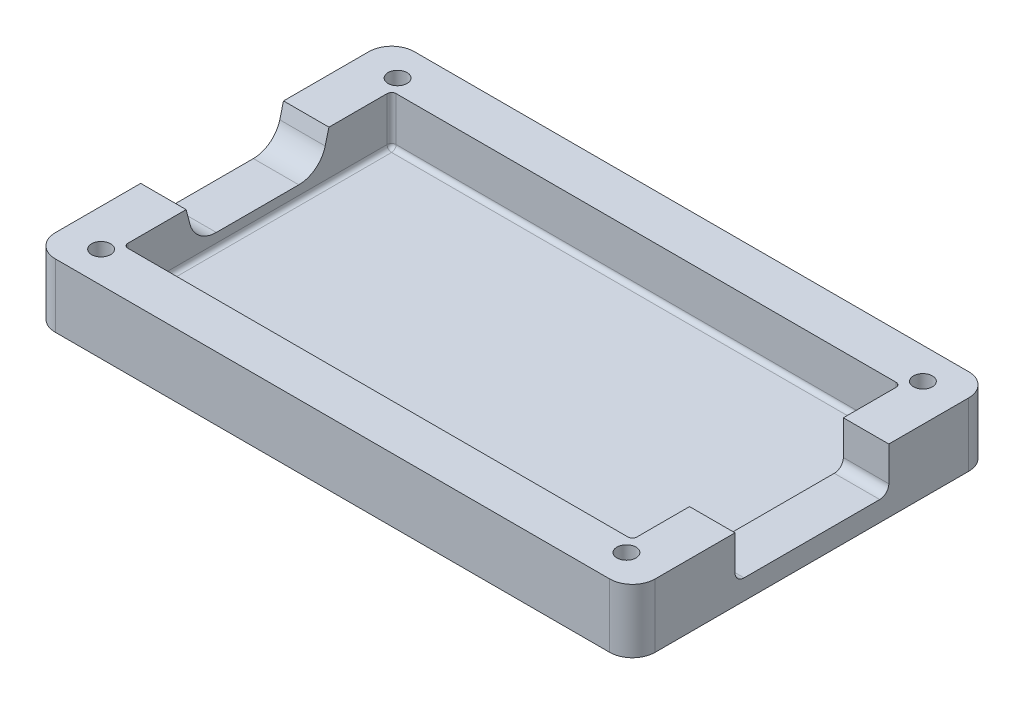
SolidWorks part; units mm, degrees
material "ABS"
ref_plane "Front Plane" through (0, 0, 0) normal (0, 0, 1) x (1, 0, 0)
ref_plane "Top Plane" through (0, 0, 0) normal (0, 1, 0) x (1, 0, 0)
ref_plane "Right Plane" through (0, 0, 0) normal (1, 0, 0) x (0, 0, -1)
sketch "Sketch1" plane through (0, 0, 0) normal (0, 1, 0) x (1, 0, 0)
  line L1 (-16.764, -10.033) -> (16.764, -10.033)
  line L2 (-16.764, -10.033) -> (-16.764, 10.033)
  line L3 (-16.764, 10.033) -> (16.764, 10.033)
  line L4 (16.764, -10.033) -> (16.764, 10.033)
  line L5 (-16.764, -10.033) -> (16.764, 10.033) construction
  line L6 (-16.764, 10.033) -> (16.764, -10.033) construction
  point P0 (0, 0)
  dimension "D1" = 20.066
  dimension "D2" = 33.528
extrude "Boss-Extrude1" add sketch "Sketch1" along normal blind 3.556
sketch "Sketch2" plane through (0, 3.556, 0) normal (0, 1, 0) x (1, 0, 0)
  line L1 (-14.224, -7.493) -> (14.224, -7.493)
  line L2 (-14.224, -7.493) -> (-14.224, 7.493)
  line L3 (-14.224, 7.493) -> (14.224, 7.493)
  line L4 (14.224, -7.493) -> (14.224, 7.493)
  line L5 (-14.224, -7.493) -> (14.224, 7.493) construction
  line L6 (-14.224, 7.493) -> (14.224, -7.493) construction
  point P0 (0, 0)
  dimension "D1" = 14.986
  dimension "D2" = 28.448
extrude "Cut-Extrude1" cut sketch "Sketch2" against normal blind 2.722
sketch "Sketch3" plane through (16.764, 0, 0) normal (1, 0, 0) x (0, 0, -1)
  line L0 (-10.033, 3.556) -> (10.033, 3.556) construction
  line L1 (-4.2995, 3.556) -> (4.2995, 3.556)
  line L2 (-4.2995, 3.556) -> (-4.2995, 1.1218)
  line L3 (-4.2995, 1.1218) -> (4.2995, 1.1218)
  line L4 (4.2995, 3.556) -> (4.2995, 1.1218)
  line L5 (-10.033, 0) -> (10.033, 0) construction
  point P6 (0, 1.1218)
  point P11 (0, 0)
extrude "Cut-Extrude2" cut sketch "Sketch3" against normal up to next
sketch "Sketch5" plane through (-16.764, 0, 0) normal (-1, 0, 0) x (0, 0, 1)
  line L0 (-3.9914, 3.556) -> (3.9914, 3.556)
  line L1 (-10.033, 3.556) -> (10.033, 3.556) construction
  line L2 (-10.033, 0) -> (10.033, 0) construction
  line L3 (-3.4845, 1.6072) -> (3.4845, 1.6072)
  line L4 (3.4845, 1.6072) -> (3.9914, 3.556)
  line L5 (-3.9914, 3.556) -> (-3.4845, 1.6072)
  point P4 (0, 3.556)
  point P7 (0, 0)
  point P8 (0, 1.6072)
extrude "Cut-Extrude3" cut sketch "Sketch5" against normal up to next
fillet "Fillet1" radius 1.524 2 edges at (-15.494, 1.6072, 3.4845) (-15.494, 1.6072, -3.4845)
fillet "Fillet2" radius 0.508 2 edges at (15.494, 1.1218, -4.2995) (15.494, 1.1218, 4.2995)
fillet "Fillet3" radius 1.27 4 edges at (-16.764, 1.778, -10.033) (-16.764, 1.778, 10.033) (16.764, 1.778, 10.033) (16.764, 1.778, -10.033)
sketch "Sketch7" plane through (0, 0, 0) normal (0, -1, 0) x (1, 0, 0)
  line L5 (-15.494, 10.033) -> (15.494, 10.033) construction
  line L9 (-14.6839, -8.2871) -> (14.6839, -8.2871) construction
  line L10 (-14.6839, -8.2871) -> (-14.6839, 8.2871) construction
  line L11 (-14.6839, 8.2871) -> (14.6839, 8.2871) construction
  line L12 (14.6839, -8.2871) -> (14.6839, 8.2871) construction
  line L13 (-14.6839, -8.2871) -> (14.6839, 8.2871) construction
  line L14 (-14.6839, 8.2871) -> (14.6839, -8.2871) construction
  circle A0 centre (-14.6839, 8.2871) radius 0.9111
  circle A1 centre (14.6839, 8.2871) radius 0.9111
  circle A2 centre (14.6839, -8.2871) radius 0.9111
  circle A3 centre (-14.6839, -8.2871) radius 0.9111
  point P0 (0, 0)
  point P10 (0, 0)
extrude "Cut-Extrude4" cut sketch "Sketch7" against normal blind 1.27
sketch "Sketch9" plane through (0, 0, 0) normal (0, -1, 0) x (1, 0, 0)
  circle A0 centre (-14.6839, 8.2871) radius 0.5309
  circle A1 centre (-14.6839, 8.2871) radius 0.9111 construction
  circle A2 centre (14.6839, 8.2871) radius 0.5309
  circle A3 centre (14.6839, -8.2871) radius 0.5309
  circle A4 centre (-14.6839, -8.2871) radius 0.5309
  circle A5 centre (14.6839, 8.2871) radius 0.9111 construction
  circle A6 centre (14.6839, -8.2871) radius 0.9111 construction
  circle A7 centre (-14.6839, -8.2871) radius 0.9111 construction
extrude "Cut-Extrude5" cut sketch "Sketch9" against normal through all
fillet "Fillet4" radius 0.254 4 edges at (14.224, 2.195, 7.493) (-14.224, 2.195, 7.493) (14.224, 2.195, -7.493) (-14.224, 2.195, -7.493)
fillet "Fillet5" radius 0.254 8 edges at (-14.1496, 0.834, 7.4186) (-14.224, 0.834, 0) (-14.1496, 0.834, -7.4186) (0, 0.834, -7.493) (14.1496, 0.834, -7.4186) (14.224, 0.834, 0) (14.1496, 0.834, 7.4186) (0, 0.834, 7.493)
equation "\"width\"=0.59"
equation "\"D1@Sketch2\"=\"width\""
equation "\"D1@Sketch1\"=\"width\"+.2"
equation "\"height\"=1.12"
equation "\"D2@Sketch2\"=\"height\""
equation "\"D2@Sketch1\"=\"height\" + .2"
